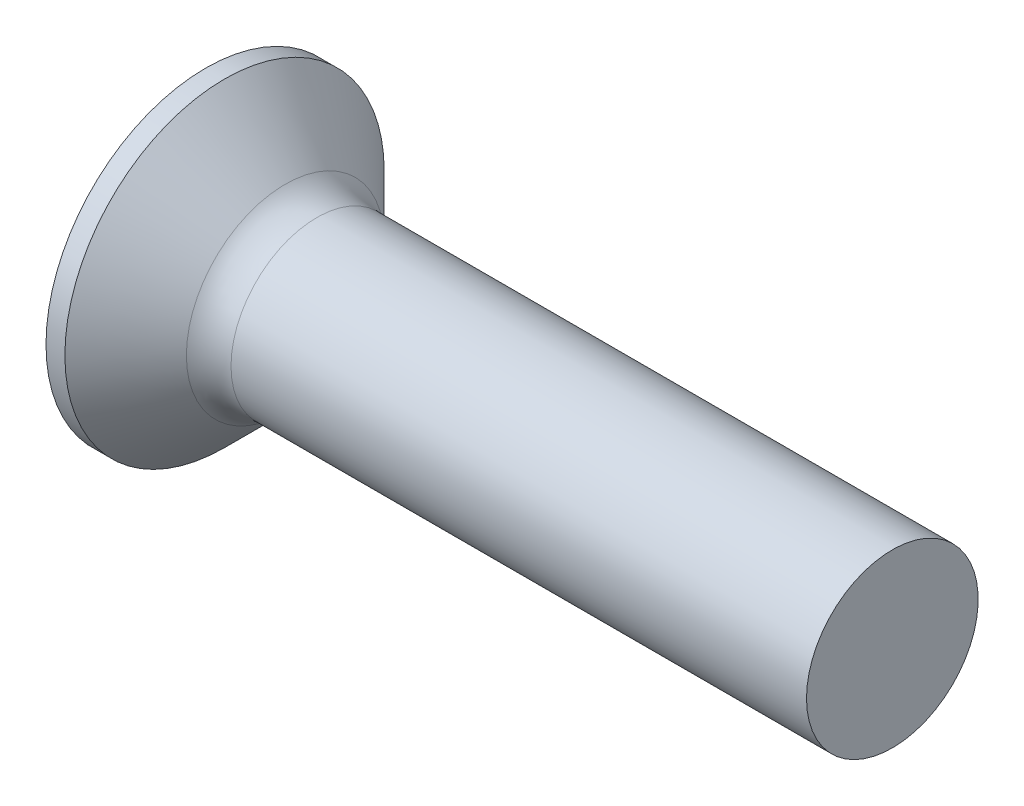
SolidWorks part; units mm, degrees
ref_plane "Plane1" through (0, 0, 0) normal (0, 0, 1) x (1, 0, 0)
ref_plane "Plane2" through (0, 0, 0) normal (0, 1, 0) x (1, 0, 0)
ref_plane "Plane3" through (0, 0, 0) normal (1, 0, 0) x (0, 0, -1)
sketch "BodySke" plane through (0, 0, 0) normal (0, 0, 1) x (1, 0, 0)
  line L0 (0, 0) -> (0, 4.65)
  line L1 (0, 4.65) -> (0.55, 4.65)
  line L2 (2.7, 2.5) -> (20, 2.5)
  line L3 (20, 2.5) -> (20, 0)
  line L4 (20, 0) -> (0, 0)
  line L5 (-6.35, 0) -> (82.55, 0) construction
  line L6 (2.7, -2.5) -> (20, -2.5) construction
  line L7 (0.55, -4.65) -> (2.7, -2.5) construction
  line L8 (0.55, 4.65) -> (2.7, 2.5)
  line L9 (0, -4.65) -> (0.55, -4.65) construction
  line L10 (3.5, 4.0875) -> (3.5, -5.4375) construction
  line L11 (0, 6.35) -> (0, -3.175) construction
  dimension "Diameter" = 5
  dimension "Length" = 20
  dimension "Head_ht" = 2.7
  dimension "Head_dia" = 9.3
  dimension "Head_ang" = 90
  dimension "D6" = 0.55
  dimension "Advance" = 0.8
  dimension "Thread_nom" = 20
revolve "Base-Revolve" add sketch "BodySke"
cosmetic thread "ThreadCosmetic" [suppressed]
fillet "Fillet1" radius 1.3 1 edges at (2.7, 0, 2.5)
sketch "Sketch3" plane through (0, 0, 0) normal (-1, 0, 0) x (0, 0, 1)
  line L0 (-0.515, 2.45) -> (0.515, 2.45)
  line L1 (0.515, 2.45) -> (0.515, -2.45)
  line L2 (0.515, -2.45) -> (-0.515, -2.45)
  line L3 (-0.515, -2.45) -> (-0.515, 2.45)
  dimension "D1" = 2.45
  dimension "Cross_dia" = 4.9
  dimension "D2" = 0.515
  dimension "Cross_width" = 1.03
ref_plane "Plane4" through (3.05, 0, 0) normal (-1, 0, 0) x (0, 0, 1)
sketch "Sketch4" plane through (3.05, 0, 0) normal (-1, 0, 0) x (0, 0, 1)
  line L0 (-0.515, 0.9293) -> (0.515, 0.9293)
  line L3 (0.515, 0.9293) -> (0.515, -0.9293)
  line L4 (0.515, -0.9293) -> (-0.515, -0.9293)
  line L5 (-0.515, -0.9293) -> (-0.515, 0.9293)
  dimension "D1" = 1.03
  dimension "D2" = 1.8587
  dimension "D3" = 0.515
  dimension "D4" = 0.9293
loft "Recess" cut profiles "Sketch3", "Sketch4"
pattern_circular "RecPat" count 2 every 90 about axis through (0, 0, 0) along (1, 0, 0) of "Recess"
sketch "RecCorSke" plane through (0, 0, 0) normal (0, 0, 1) x (1, 0, 0)
  line L0 (-3.175, 0) -> (15.875, 0) construction
  line L2 (0, 0) -> (0, 1.0643)
  line L3 (0, 1.0643) -> (3.05, 0.851)
  line L4 (3.05, 0.851) -> (3.3265, 0)
  line L5 (3.3265, 0) -> (0, 0)
  dimension "Diameter" = 1.702
  dimension "Depth" = 3.05
  dimension "Draft_angle" = 4
  dimension "Bottom_angle" = 18
revolve "RecessCore" cut sketch "RecCorSke" angle 360 about L0
sketch "ThdSchSke" plane through (0, 0, 0) normal (0, 0, 1) x (1, 0, 0)
  line L0 (3.5, -2.055) -> (3.1884, -2.5)
  line L1 (3.5, -2.055) -> (3.8116, -2.5)
  line L2 (3.8116, -2.5) -> (3.8116, -3.125)
  line L3 (-3.175, 0) -> (5.1513, 0) construction
  line L5 (3.8116, -3.125) -> (3.1884, -3.125)
  line L6 (3.1884, -3.125) -> (3.1884, -2.5)
  line L7 (0, 4.65) -> (0, -4.65) construction
  dimension "Thread_minor" = 4.11
  dimension "Diameter" = 5
  dimension "Start" = 3.5
  dimension "SideAngle" = 55
  dimension "VeeAngle" = 70
  dimension "Overcut" = 6.25
revolve "ThreadSchematic" [suppressed] cut sketch "ThdSchSke" angle 360 about L3
pattern_linear "ThdSchPat" [suppressed]
equation "\"D1@Sketch3\" = \"Cross_dia@Sketch3\" / 2"
equation "\"D2@Sketch3\" = \"Cross_width@Sketch3\" / 2"
equation "\"Depth@RecCorSke\" = \"Cross_depth@Plane4\""
equation "\"D1@Sketch4\" = \"Cross_width@Sketch3\""
equation "\"D2@Sketch4\" = \"Cross_dia@Sketch3\" - 2.0 * \"Cross_depth@Plane4\" * tan(26.5  * 0.017453292)"
equation "\"D3@Sketch4\" = \"D1@Sketch4\" / 2"
equation "\"D4@Sketch4\" = \"D2@Sketch4\" / 2"
equation "\"Thread_length@ThreadCosmetic\" = ((sgn( (\"Length@BodySke\" - \"Advance@BodySke\" * 1.0 - \"Head_ht@BodySke\" ) - \"Thread_nom@BodySke\" )-1)*( (\"Length@BodySke\" - \"Advance@BodySke\" * 1.0 - \"Head_ht@BodySke\" ) - \"Thread_nom@BodySke\" ))/-2+ \"Thread_nom@BodySke\""
equation "\"Thread_minor@ThdSchSke\" = \"Thread_minor@ThreadCosmetic\""
equation "\"Diameter@ThdSchSke\" = \"Diameter@BodySke\""
equation "\"Overcut@ThdSchSke\" = \"Diameter@BodySke\" * 1.25"
equation "\"Start@ThdSchSke\" = 0.000001 + \"Length@BodySke\" - \"Thread_length@ThreadCosmetic\"  '---Countersunk---"
equation "\"Num_threads@ThdSchPat\" = int( \"Thread_length@ThreadCosmetic\" / \"Advance@BodySke\" + 0.999 )  + 1"
equation "\"Advance@ThdSchPat\" = \"Thread_length@ThreadCosmetic\" /  (\"Num_threads@ThdSchPat\" - 1) 'relax it"
